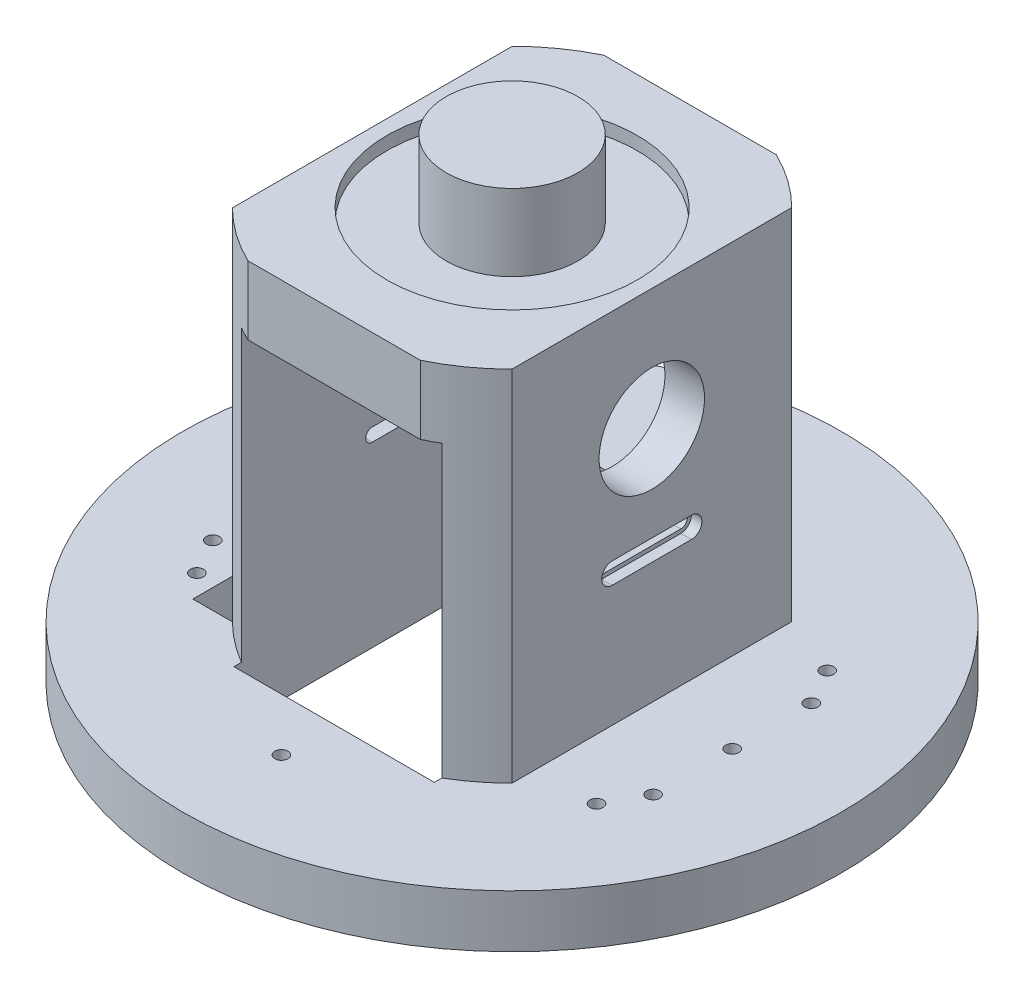
SolidWorks part; units mm, degrees
ref_plane "Front Plane" through (0, 0, 0) normal (0, 0, 1) x (1, 0, 0)
ref_plane "Top Plane" through (0, 0, 0) normal (0, 1, 0) x (1, 0, 0)
ref_plane "Right Plane" through (0, 0, 0) normal (1, 0, 0) x (0, 0, -1)
sketch "Sketch1" plane through (0, 0, 0) normal (0, 1, 0) x (1, 0, 0)
  circle A0 centre (0, 0) radius 125
  dimension "D1" = 250
extrude "Boss-Extrude1" add sketch "Sketch1" along normal blind 20
sketch "Sketch2" plane through (0, 20, 0) normal (0, 1, 0) x (1, 0, 0)
  line L1 (-53, 67.5) -> (53, 67.5)
  line L2 (-53, 67.5) -> (-53, -67.5)
  line L3 (-53, -67.5) -> (53, -67.5)
  line L4 (53, 67.5) -> (53, -67.5)
  line L5 (-53, 67.5) -> (53, -67.5) construction
  line L6 (-53, -67.5) -> (53, 67.5) construction
  point P0 (0, 0)
  dimension "D1" = 106
  dimension "D2" = 135
extrude "Boss-Extrude2" add sketch "Sketch2" along normal blind 160
sketch "Sketch5" plane through (53, 0, 0) normal (1, 0, 0) x (0, 0, -1)
  circle A0 centre (0, 110) radius 67.5 construction
  circle A1 centre (0, 110) radius 20
  dimension "D1" = 135
  dimension "D3" = 40
  dimension "D2" = 110
extrude "Cut-Extrude2" cut sketch "Sketch5" against normal through all
sketch "Sketch6" plane through (0, 0, 0) normal (0, -1, 0) x (1, 0, 0)
  line L1 (-38, 67.5) -> (38, 67.5)
  line L2 (-38, 67.5) -> (-38, -67.5)
  line L3 (-38, -67.5) -> (38, -67.5)
  line L4 (38, 67.5) -> (38, -67.5)
  line L5 (-38, 67.5) -> (38, -67.5) construction
  line L6 (-38, -67.5) -> (38, 67.5) construction
  point P0 (0, 0)
  dimension "D1" = 135
  dimension "D2" = 76
extrude "Cut-Extrude3" cut sketch "Sketch6" against normal blind 130
sketch "Sketch7" plane through (0, 180, 0) normal (0, 1, 0) x (1, 0, 0)
  line L0 (53, -67.5) -> (53, 67.5) construction
  line L1 (-53, 67.5) -> (53, 67.5)
  line L2 (-53, 67.5) -> (-53, -67.5)
  line L3 (-53, -67.5) -> (53, -67.5)
  line L4 (53, 67.5) -> (53, -67.5)
  line L5 (-53, 67.5) -> (53, -67.5) construction
  line L6 (-53, -67.5) -> (53, 67.5) construction
  circle A0 centre (0, 0) radius 47.5 construction
  circle A1 centre (0, 0) radius 25
  dimension "D1" = 95
  dimension "D2" = 50
  dimension "D3" = 135
extrude "Cut-Extrude5" cut sketch "Sketch7" against normal blind 29
sketch "Sketch10" plane through (0, 151, 0) normal (0, 1, 0) x (1, 0, 0)
  line L1 (-53, 67.5) -> (53, 67.5)
  line L2 (-53, 67.5) -> (-53, -67.5)
  line L3 (-53, -67.5) -> (53, -67.5)
  line L4 (53, 67.5) -> (53, -67.5)
  line L5 (-53, 67.5) -> (53, -67.5) construction
  line L6 (-53, -67.5) -> (53, 67.5) construction
  circle A0 centre (0, 0) radius 47.5
  dimension "D1" = 95
extrude "Boss-Extrude4" add sketch "Sketch10" along normal blind 5
sketch "Sketch11" plane through (0, 0, 0) normal (0, -1, 0) x (-1, 0, 0)
  line L0 (0, 125) -> (0, -125) construction
  line L1 (83.5029, 0) -> (0, 0) construction
  line L2 (0, 0) -> (-83.5029, 0) construction
  circle A0 centre (0, 0) radius 125 construction
  circle A1 centre (83.5029, 0) radius 2.5
  circle A2 centre (-83.5029, 0) radius 2.5
  circle A3 centre (83.5029, -30) radius 2.5
  circle A4 centre (83.5029, 30) radius 2.5
  circle A5 centre (-83.5029, 30) radius 2.5
  circle A6 centre (-83.5029, -30) radius 2.5
  point P21 (-163.4606, 100.5433)
  dimension "D1" = 5
  dimension "D2" = 5
  dimension "D3" = 167.0059
  dimension "D4" = 30
  dimension "D5" = 30
extrude "Cut-Extrude6" cut sketch "Sketch11" against normal through all
sketch "Sketch12" plane through (0, 0, 0) normal (0, -1, 0) x (-1, 0, 0)
  circle A0 centre (0, 0) radius 87.5 construction
  circle A2 centre (0, 87.5) radius 2.5
  circle A10 centre (75.7772, 43.75) radius 2.5
  circle A11 centre (75.7772, -43.75) radius 2.5
  circle A12 centre (0, -87.5) radius 2.5
  circle A13 centre (-75.7772, -43.75) radius 2.5
  circle A14 centre (-75.7772, 43.75) radius 2.5
  point P17 (0, 0)
  point P21 (0, 0)
  dimension "D1" = 175
  dimension "D2" = 5
  dimension "D3" = 6
extrude "Cut-Extrude7" cut sketch "Sketch12" against normal through all
sketch "Sketch13" plane through (0, 0, 0) normal (0, -1, 0) x (-1, 0, 0)
  circle A0 centre (0, -87.5) radius 5
  circle A1 centre (-75.7772, -43.75) radius 5
  circle A2 centre (-75.7772, 43.75) radius 5
  circle A5 centre (0, 87.5) radius 5
  circle A6 centre (75.7772, 43.75) radius 5
  circle A7 centre (75.7772, -43.75) radius 5
  dimension "D1" = 10
extrude "Cut-Extrude8" cut sketch "Sketch13" against normal blind 5
sketch "Sketch14" plane through (0, 156, 0) normal (0, 1, 0) x (1, 0, 0)
  circle A0 centre (0, 0) radius 75
  circle A1 centre (0, 0) radius 94.4551
  dimension "D1" = 150
extrude "Cut-Extrude10" cut sketch "Sketch14" against normal up to surface (136 mm away) up to face at (75.7772, 20, 46.25)
sketch "Sketch15" plane through (0, 20, 0) normal (0, 1, 0) x (1, 0, 0)
  line L5 (-53, 53.066) -> (-68, 53.066)
  line L6 (-53, 53.066) -> (-53, -53.066)
  line L7 (-53, -53.066) -> (-68, -53.066)
  line L8 (-68, 53.066) -> (-68, -53.066)
  dimension "D1" = 15
extrude "Cut-Extrude11" cut sketch "Sketch15" against normal blind 20
sketch "Sketch16" plane through (-38, 0, 0) normal (1, 0, 0) x (0, 0, -1)
  line L0 (-15, 70) -> (15, 70) construction
  line L1 (-15, 72.5) -> (15, 72.5)
  line L2 (-15, 67.5) -> (15, 67.5)
  line L3 (0, 130) -> (64.6607, 130) construction
  arc A0 (-15, 72.5) -> (-15, 67.5) centre (-15, 70) ccw
  arc A1 (15, 67.5) -> (15, 72.5) centre (15, 70) ccw
  point P2 (0, 70)
  dimension "D2" = 2.5
  dimension "D1" = 30
  dimension "D3" = 60
extrude "Cut-Extrude12" cut sketch "Sketch16" against normal through all both and the other way through all
sketch "Sketch17" plane through (-53, 0, 0) normal (-1, 0, 0) x (0, 0, 1)
  line L0 (-15, 70) -> (15, 70) construction
  line L1 (-15, 74) -> (15, 74)
  line L2 (-15, 66) -> (15, 66)
  arc A0 (-15, 74) -> (-15, 66) centre (-15, 70) ccw
  arc A1 (15, 66) -> (15, 74) centre (15, 70) ccw
  point P4 (0, 70)
  dimension "D1" = 4
extrude "Cut-Extrude13" cut sketch "Sketch17" against normal blind 4
mirror "Mirror1" about plane through (0, 0, 0) normal (1, 0, 0) of "Cut-Extrude13"
